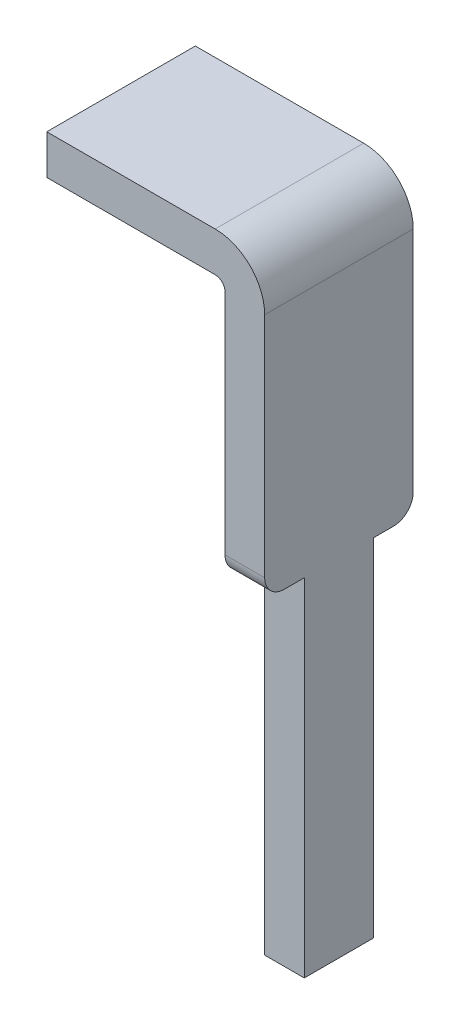
SolidWorks part; units mm, degrees
ref_plane "Front Plane" through (0, 0, 0) normal (0, 0, 1) x (1, 0, 0)
ref_plane "Top Plane" through (0, 0, 0) normal (0, 1, 0) x (1, 0, 0)
ref_plane "Right Plane" through (0, 0, 0) normal (1, 0, 0) x (0, 0, -1)
sketch "Sketch2" plane through (0, 0, 0) normal (0, 0, 1) x (1, 0, 0)
  line L0 (0, 0) -> (3, 0)
  line L1 (3.5, -0.5) -> (3.5, -6.5)
  line L2 (0, -0.4) -> (3, -0.4)
  line L3 (3.1, -0.5) -> (3.1, -6.5)
  line L4 (0, -0.4) -> (0, 0)
  line L5 (3.1, -6.5) -> (3.5, -6.5)
  arc A0 (3, 0) -> (3.5, -0.5) centre (3, -0.5) cw
  arc A1 (3, -0.4) -> (3.1, -0.5) centre (3, -0.5) cw
  dimension "D1" = 0.5
  dimension "D2" = 3
  dimension "D3" = 6
  dimension "D4" = 0.4
extrude "Boss-Extrude1" add sketch "Sketch2" along normal blind 1.5
sketch "Sketch3" plane through (3.5, 0, 0) normal (1, 0, 0) x (0, 0, -1)
  line L0 (-0.75, -6.5) -> (-0.75, -0.5) construction
  line L1 (-1.5, -6.5) -> (0, -6.5) construction
  line L2 (-1.5, -0.5) -> (0, -0.5) construction
  line L3 (0, -6.5) -> (-0.4, -6.5)
  line L4 (-1.5, -6.5) -> (-1.1, -6.5)
  line L5 (-1.5, -6.5) -> (-1.5, -3)
  line L6 (-1.5, -3) -> (-1.1, -3)
  line L7 (-1.1, -6.5) -> (-1.1, -3)
  line L8 (0, -6.5) -> (0, -3)
  line L9 (-0.4, -6.5) -> (-0.4, -3)
  line L10 (0, -3) -> (-0.4, -3)
  dimension "D1" = 3.5
  dimension "D2" = 0.35
extrude "Cut-Extrude1" cut sketch "Sketch3" against normal blind 1.5
fillet "Fillet2" radius 0.2 2 edges at (3.3, -3, 1.5) (3.3, -3, 0)
sketch "Sketch4" plane through (0, 0, 0) normal (-1, 0, 0) x (0, 0, 1)
  line L0 (1.5, 0) -> (1.5, -0.4) construction
  line L1 (1.5, -0.4) -> (0, -0.4) construction
  line L2 (0, 0) -> (0, -0.4) construction
  line L3 (1.5, 0) -> (0, 0) construction
  line L4 (1.5, 0) -> (1.5, -0.4)
  line L5 (1.5, -0.4) -> (0, -0.4)
  line L6 (0, 0) -> (0, -0.4)
  line L7 (1.5, 0) -> (0, 0)
extrude "Cut-Extrude2" cut sketch "Sketch4" against normal blind 1.3
